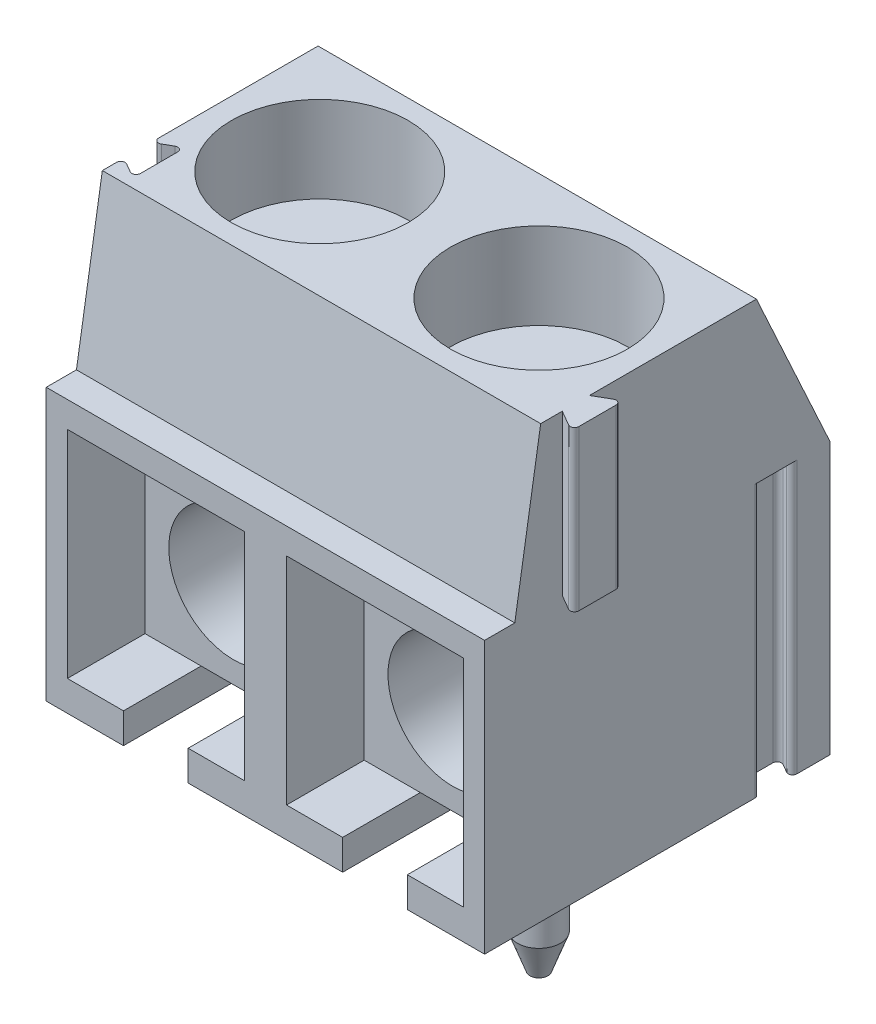
SolidWorks part; units mm, degrees
ref_plane "Front Plane" through (0, 0, 0) normal (0, 0, 1) x (1, 0, 0)
ref_plane "Top Plane" through (0, 0, 0) normal (0, 1, 0) x (1, 0, 0)
ref_plane "Right Plane" through (0, 0, 0) normal (1, 0, 0) x (0, 0, -1)
ref_plane "Plane1" through (0, 0, 0) normal (1, 0, 0) x (0, 0, -1)
sketch "Sketch1" plane through (0, 0, 0) normal (1, 0, 0) x (0, 0, -1)
  line L0 (-8, 0) -> (0, 0)
  line L1 (0, 0) -> (0, 6.3)
  line L2 (0, 6.3) -> (-1.7, 10)
  line L3 (-1.7, 10) -> (-6.7, 10)
  line L4 (-6.7, 10) -> (-7.3, 6.3)
  line L5 (-7.3, 6.3) -> (-8, 6.3)
  line L6 (-8, 6.3) -> (-8, 0)
extrude "Boss-Extrude1" add sketch "Sketch1" along normal blind 10.16
ref_plane "Plane2" through (0, 0, 8) normal (0, 0, 1) x (1, 0, 0)
sketch "Sketch2" plane through (0, 0, 8) normal (0, 0, 1) x (1, 0, 0)
  line L0 (0.49, 0.7) -> (4.59, 0.7)
  line L1 (4.59, 0.7) -> (4.59, 5.7)
  line L2 (4.59, 5.7) -> (0.49, 5.7)
  line L3 (0.49, 5.7) -> (0.49, 0.7)
extrude "Cut-Extrude1" cut sketch "Sketch2" against normal blind 5.8
ref_plane "Plane3" through (0, 0, 8) normal (0, 0, 1) x (1, 0, 0)
sketch "Sketch3" plane through (0, 0, 8) normal (0, 0, 1) x (1, 0, 0)
  line L0 (5.57, 0.7) -> (9.67, 0.7)
  line L1 (9.67, 0.7) -> (9.67, 5.7)
  line L2 (9.67, 5.7) -> (5.57, 5.7)
  line L3 (5.57, 5.7) -> (5.57, 0.7)
extrude "Cut-Extrude2" cut sketch "Sketch3" against normal blind 5.8
ref_plane "Plane4" through (0, 0, 0) normal (0, 1, 0) x (-1, 0, 0)
sketch "Sketch4" plane through (0, 0, 0) normal (0, 1, 0) x (-1, 0, 0)
  line L0 (-1.79, 4.2) -> (-1.79, 8)
  line L1 (-1.79, 8) -> (-3.29, 8)
  line L2 (-3.29, 8) -> (-3.29, 4.2)
  arc A0 (-3.29, 4.2) -> (-1.79, 4.2) centre (-2.54, 4.2) ccw
extrude "Cut-Extrude3" cut sketch "Sketch4" along normal blind 1
ref_plane "Plane5" through (0, 0, 0) normal (0, 1, 0) x (-1, 0, 0)
sketch "Sketch5" plane through (0, 0, 0) normal (0, 1, 0) x (-1, 0, 0)
  line L0 (-6.87, 4.2) -> (-6.87, 8)
  line L1 (-6.87, 8) -> (-8.37, 8)
  line L2 (-8.37, 8) -> (-8.37, 4.2)
  arc A0 (-8.37, 4.2) -> (-6.87, 4.2) centre (-7.62, 4.2) ccw
extrude "Cut-Extrude4" cut sketch "Sketch5" along normal blind 1
ref_plane "Plane6" through (0, 0, 4.2) normal (0, 0, 1) x (1, 0, 0)
sketch "Sketch6" plane through (0, 0, 4.2) normal (0, 0, 1) x (1, 0, 0)
  line L0 (0.49, 0.7) -> (4.59, 0.7)
  line L1 (4.59, 0.7) -> (4.59, 5.4)
  line L2 (4.59, 5.4) -> (0.49, 5.4)
  line L3 (0.49, 5.4) -> (0.49, 0.7)
  circle A0 centre (2.54, 2.7) radius 1.5
extrude "Boss-Extrude2" add sketch "Sketch6" against normal blind 2 and the other way blind 2
ref_plane "Plane7" through (0, 0, 4.2) normal (0, 0, 1) x (1, 0, 0)
sketch "Sketch7" plane through (0, 0, 4.2) normal (0, 0, 1) x (1, 0, 0)
  line L0 (5.57, 0.7) -> (9.67, 0.7)
  line L1 (9.67, 0.7) -> (9.67, 5.4)
  line L2 (9.67, 5.4) -> (5.57, 5.4)
  line L3 (5.57, 5.4) -> (5.57, 0.7)
  circle A0 centre (7.62, 2.7) radius 1.5
extrude "Boss-Extrude3" add sketch "Sketch7" against normal blind 2 and the other way blind 2
ref_plane "Plane8" through (0, 0, 4.2) normal (0, 0, 1) x (1, 0, 0)
sketch "Sketch8" plane through (0, 0, 4.2) normal (0, 0, 1) x (1, 0, 0)
  line L0 (2.54, 0.7) -> (3.04, 0.7)
  line L1 (3.04, 0.7) -> (3.04, -2.7)
  line L2 (3.04, -2.7) -> (2.7488, -3.5)
  line L3 (2.7488, -3.5) -> (2.54, -3.5)
  line L4 (2.54, -3.5) -> (2.54, 0.7)
  line L5 (2.54, -3.5) -> (2.54, 0.7) construction
revolve "Revolve1" add sketch "Sketch8" angle 360 about L5
ref_plane "Plane9" through (0, 0, 4.2) normal (0, 0, 1) x (1, 0, 0)
sketch "Sketch9" plane through (0, 0, 4.2) normal (0, 0, 1) x (1, 0, 0)
  line L0 (7.62, 0.7) -> (8.12, 0.7)
  line L1 (8.12, 0.7) -> (8.12, -2.7)
  line L2 (8.12, -2.7) -> (7.8288, -3.5)
  line L3 (7.8288, -3.5) -> (7.62, -3.5)
  line L4 (7.62, -3.5) -> (7.62, 0.7)
  line L5 (7.62, -3.5) -> (7.62, 0.7) construction
revolve "Revolve2" add sketch "Sketch9" angle 360 about L5
ref_plane "Plane10" through (0, 0, 4.2) normal (0, 0, 1) x (1, 0, 0)
sketch "Sketch10" plane through (0, 0, 4.2) normal (0, 0, 1) x (1, 0, 0)
  line L0 (2.54, 10) -> (4.59, 10)
  line L1 (4.59, 10) -> (4.59, 8)
  line L2 (4.59, 8) -> (2.54, 8)
  line L3 (2.54, 8) -> (2.54, 10)
  line L4 (2.54, 8) -> (2.54, 10) construction
revolve "Cut-Revolve1" cut sketch "Sketch10" angle 360 about L4
ref_plane "Plane11" through (0, 0, 4.2) normal (0, 0, 1) x (1, 0, 0)
sketch "Sketch11" plane through (0, 0, 4.2) normal (0, 0, 1) x (1, 0, 0)
  line L0 (7.62, 10) -> (9.67, 10)
  line L1 (9.67, 10) -> (9.67, 8)
  line L2 (9.67, 8) -> (7.62, 8)
  line L3 (7.62, 8) -> (7.62, 10)
  line L4 (7.62, 8) -> (7.62, 10) construction
revolve "Cut-Revolve2" cut sketch "Sketch11" angle 360 about L4
ref_plane "Plane12" through (0, 0, 0) normal (0, 1, 0) x (-1, 0, 0)
sketch "Sketch12" plane through (0, 0, 0) normal (0, 1, 0) x (-1, 0, 0)
  line L0 (0.35, 1.7671) -> (0, 1.565)
  line L1 (0, 1.565) -> (0, 0.935)
  line L2 (0, 0.935) -> (0.35, 0.7329)
  line L3 (0.5, 0.8195) -> (0.5, 1.6805)
  arc A0 (0.5, 1.6805) -> (0.35, 1.7671) centre (0.4, 1.6805) ccw
  arc A1 (0.35, 0.7329) -> (0.5, 0.8195) centre (0.4, 0.8195) ccw
extrude "Boss-Extrude4" add sketch "Sketch12" along normal blind 6.3
ref_plane "Plane13" through (0, 0, 0) normal (0, 1, 0) x (-1, 0, 0)
sketch "Sketch13" plane through (0, 0, 0) normal (0, 1, 0) x (-1, 0, 0)
  line L0 (-9.81, 1.7671) -> (-10.01, 1.6516)
  line L1 (-10.16, 1.7382) -> (-10.16, 1.865)
  line L2 (-10.16, 1.865) -> (-10.46, 1.865)
  line L3 (-10.46, 1.865) -> (-10.46, 0.635)
  line L4 (-10.46, 0.635) -> (-10.16, 0.635)
  line L5 (-10.16, 0.635) -> (-10.16, 0.7618)
  line L6 (-10.01, 0.8484) -> (-9.81, 0.7329)
  line L7 (-9.66, 0.8195) -> (-9.66, 1.6805)
  arc A0 (-9.66, 1.6805) -> (-9.81, 1.7671) centre (-9.76, 1.6805) ccw
  arc A1 (-10.01, 1.6516) -> (-10.16, 1.7382) centre (-10.06, 1.7382) cw
  arc A2 (-10.16, 0.7618) -> (-10.01, 0.8484) centre (-10.06, 0.7618) cw
  arc A3 (-9.81, 0.7329) -> (-9.66, 0.8195) centre (-9.76, 0.8195) ccw
extrude "Cut-Extrude5" cut sketch "Sketch13" along normal blind 6.3
ref_plane "Plane14" through (0, 10, 0) normal (0, 1, 0) x (-1, 0, 0)
sketch "Sketch14" plane through (0, 10, 0) normal (0, 1, 0) x (-1, 0, 0)
  line L0 (0.2, 6.4) -> (0, 6.4)
  line L1 (0, 6.4) -> (0, 6.3732)
  line L2 (-0.15, 6.2866) -> (-0.35, 6.4021)
  line L3 (-0.5, 6.3155) -> (-0.5, 5.4545)
  line L4 (-0.35, 5.3679) -> (-0.15, 5.4834)
  line L5 (0, 5.3968) -> (0, 5.37)
  line L6 (0, 5.37) -> (0.2, 5.37)
  line L7 (0.2, 5.37) -> (0.2, 6.4)
  arc A0 (0, 6.3732) -> (-0.15, 6.2866) centre (-0.1, 6.3732) cw
  arc A1 (-0.35, 6.4021) -> (-0.5, 6.3155) centre (-0.4, 6.3155) ccw
  arc A2 (-0.5, 5.4545) -> (-0.35, 5.3679) centre (-0.4, 5.4545) ccw
  arc A3 (-0.15, 5.4834) -> (0, 5.3968) centre (-0.1, 5.3968) cw
extrude "Cut-Extrude6" cut sketch "Sketch14" against normal blind 3.7
ref_plane "Plane15" through (0, 10, 0) normal (0, 1, 0) x (-1, 0, 0)
sketch "Sketch15" plane through (0, 10, 0) normal (0, 1, 0) x (-1, 0, 0)
  line L0 (-10.16, 6.2) -> (-10.51, 6.4021)
  line L1 (-10.66, 6.3155) -> (-10.66, 5.4545)
  line L2 (-10.51, 5.3679) -> (-10.16, 5.57)
  line L3 (-10.16, 5.57) -> (-10.16, 6.2)
  arc A0 (-10.51, 6.4021) -> (-10.66, 6.3155) centre (-10.56, 6.3155) ccw
  arc A1 (-10.66, 5.4545) -> (-10.51, 5.3679) centre (-10.56, 5.4545) ccw
extrude "Boss-Extrude5" add sketch "Sketch15" against normal blind 3.7
